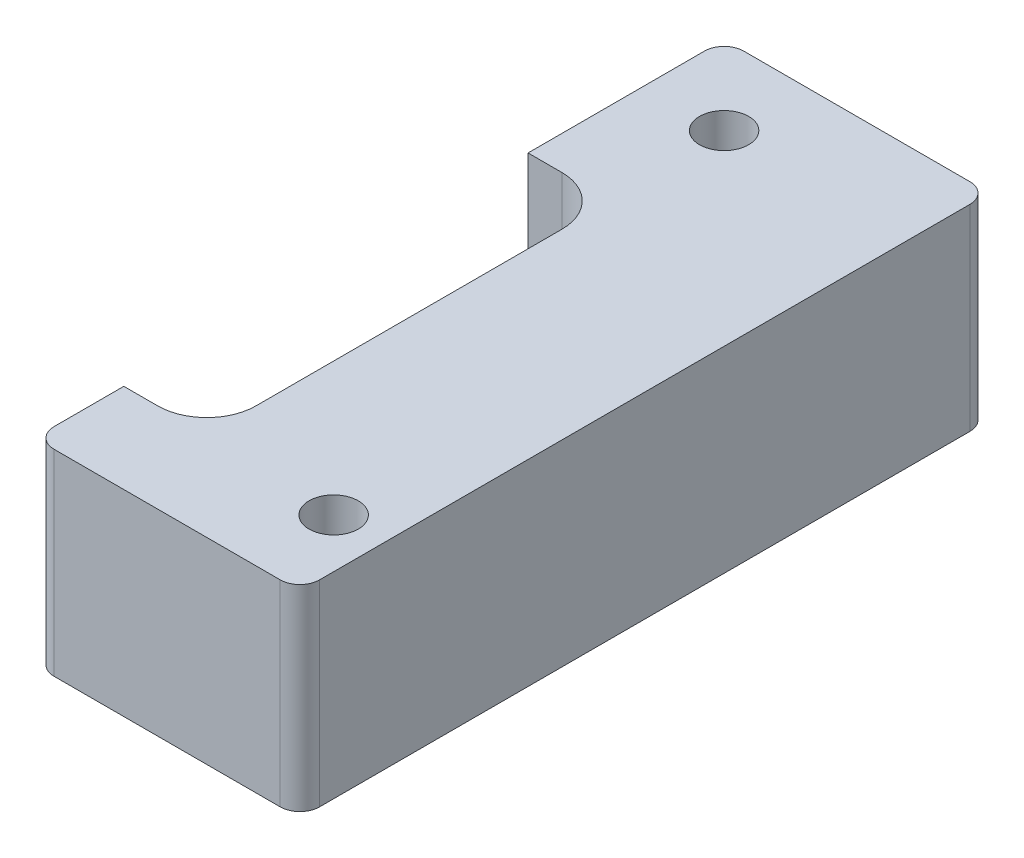
SolidWorks part; units mm, degrees
material "Пластичное железо"
ref_plane "Спереди" through (0, 0, 0) normal (0, 0, 1) x (1, 0, 0)
ref_plane "Сверху" through (0, 0, 0) normal (0, 1, 0) x (1, 0, 0)
ref_plane "Справа" through (0, 0, 0) normal (1, 0, 0) x (0, 0, -1)
sketch "Эскиз1" plane through (0, 0, 0) normal (0, 1, 0) x (1, 0, 0)
  line L1 (-6.75, -16.5337) -> (-6.75, -17.5337)
  line L3 (-6.75, -17.5337) -> (1.25, -17.5337)
  line L6 (1.25, -17.5337) -> (5.75, -17.5337)
  line L8 (-5.75, -9.4615) -> (-5.7467, -9.4615)
  line L9 (-4.7467, -8.4615) -> (-4.7467, 3.5385)
  line L10 (-5.75, 4.5385) -> (-5.7467, 4.5385)
  line L11 (-5.75, 17.5385) -> (5.75, 17.5385)
  line L12 (-6.75, 16.5385) -> (-6.75, 5.5385)
  line L13 (-6.75, -10.4615) -> (-6.75, -16.5337)
  line L14 (6.75, 16.5385) -> (6.75, -16.5337)
  circle A2 centre (-2.75, 13.5385) radius 1.25
  circle A3 centre (4.25, -13.3168) radius 1.25
  arc A4 (6.75, -16.5337) -> (5.75, -17.5337) centre (5.75, -16.5337) cw
  arc A8 (-6.75, -10.4615) -> (-5.75, -9.4615) centre (-5.75, -10.4615) cw
  arc A9 (-4.7467, -8.4615) -> (-5.7467, -9.4615) centre (-5.7467, -8.4615) cw
  arc A10 (5.75, 17.5385) -> (6.75, 16.5385) centre (5.75, 16.5385) cw
  arc A11 (-5.7467, 4.5385) -> (-4.7467, 3.5385) centre (-5.7467, 3.5385) cw
  arc A12 (-6.75, 5.5385) -> (-5.75, 4.5385) centre (-5.75, 5.5385) ccw
  arc A13 (-6.75, 16.5385) -> (-5.75, 17.5385) centre (-5.75, 16.5385) cw
extrude "Бобышка-Вытянуть2" add sketch "Эскиз1" along normal blind 10
sketch "Sketch1" plane through (0, 0, 0) normal (0, -1, 0) x (1, 0, 0)
  line L0 (-3.41, -6.5685) -> (-16.25, -6.5685) construction
  line L1 (-2.5287, -7.5685) -> (-7.75, -7.5685) construction
  line L6 (-7.75, -18.5385) -> (-7.75, 21.3168) construction
  line L7 (-7.75, 12.9875) -> (-2.5287, 12.9875)
  line L8 (-7.75, 12.9875) -> (-7.75, -7.5685)
  line L9 (-7.75, -7.5685) -> (-2.5287, -7.5685)
  line L10 (-2.5287, 12.9875) -> (-2.5287, -7.5685)
  line L11 (-7.75, 11.9875) -> (-15.75, 11.9875) construction
  dimension "D1" = 1
  dimension "D2" = 1
extrude "Cut-Extrude1" cut sketch "Sketch1" against normal up to surface (10 mm away) up to face at (-2.6686, 10, 0.1955)
fillet "Fillet1" radius 1 1 edges at (-6.75, 5, 17.5337)
fillet "Fillet2" radius 2.5 2 edges at (-2.5287, 5, -7.5685) (-2.5287, 5, 12.9875)
